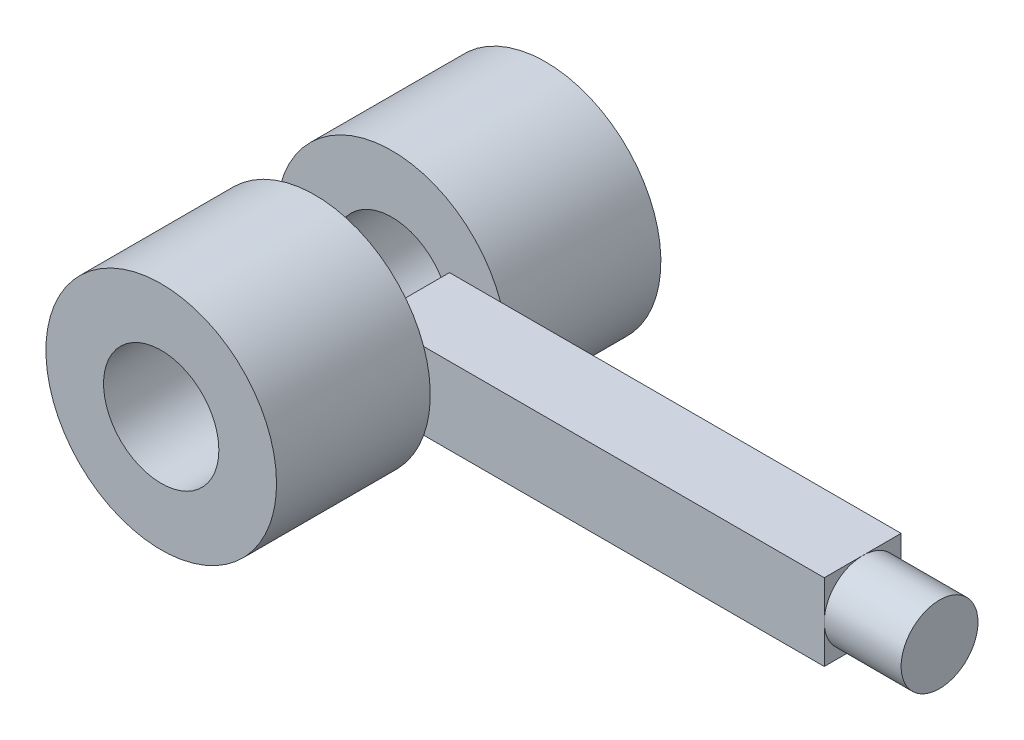
SolidWorks part; units mm, degrees
ref_plane "Front Plane" through (0, 0, 0) normal (0, 0, 1) x (1, 0, 0)
ref_plane "Top Plane" through (0, 0, 0) normal (0, 1, 0) x (1, 0, 0)
ref_plane "Right Plane" through (0, 0, 0) normal (1, 0, 0) x (0, 0, -1)
sketch "Sketch1" plane through (0, 0, 0) normal (0, 0, 1) x (1, 0, 0)
  circle A0 centre (0, 0) radius 3
  circle A1 centre (0, 0) radius 1.5
  dimension "D1" = 6
  dimension "D2" = 3
extrude "Boss-Extrude1" add sketch "Sketch1" along normal blind 4
ref_plane "Plane1" through (0, 0, -2) normal (0, 0, -1) x (-1, 0, 0)
sketch "Sketch2" plane through (0, 0, -2) normal (0, 0, -1) x (-1, 0, 0)
  circle A0 centre (0, 0) radius 1.5 construction
  circle A1 centre (0, 0) radius 3
  circle A2 centre (0, 0) radius 3
  circle A3 centre (0, 0) radius 1.5
  dimension "D1" = 0
extrude "Boss-Extrude2" add sketch "Sketch2" along normal blind 4 separate body
sketch "Sketch3" plane through (0, 0, -2) normal (0, 0, 1) x (1, 0, 0)
  line L1 (2.5, -1) -> (1.5, -1)
  line L2 (2.5, -1) -> (2.5, 1)
  line L3 (2.5, 1) -> (1.5, 1)
  line L4 (1.5, -1) -> (1.5, 1)
  line L5 (2.5, -1) -> (1.5, 1) construction
  line L6 (2.5, 1) -> (1.5, -1) construction
  circle A0 centre (0, 0) radius 1.5 construction
  point P7 (0, 0)
  point P8 (0, 0)
  point P10 (0, 0)
  dimension "D1" = 1
  dimension "D2" = 2
  dimension "D3" = 1
extrude "Boss-Extrude3" add sketch "Sketch3" along normal up to next
sketch "Sketch4" plane through (2.5, 0, 0) normal (1, 0, 0) x (0, 0, -1)
  line L4 (0, 1) -> (0, -1)
  line L5 (0, -1) -> (2, -1)
  line L6 (2, -1) -> (2, 1)
  line L7 (2, 1) -> (0, 1)
  line L8 (0, 1) -> (0, -1)
  line L9 (0, -1) -> (2, -1)
  line L10 (2, -1) -> (2, 1)
  line L11 (2, 1) -> (0, 1)
  dimension "D1" = 0
extrude "Boss-Extrude4" add sketch "Sketch4" along normal blind 10.75
sketch "Sketch6" plane through (13.25, 0, 0) normal (1, 0, 0) x (0, 0, -1)
  line L0 (2, 1) -> (0, 1) construction
  line L1 (2, -3.2056) -> (2, 3.2056) construction
  circle A0 centre (1, 0) radius 1
  dimension "D3" = 2
  dimension "D1" = 1
  dimension "D2" = 1
extrude "Boss-Extrude5" add sketch "Sketch6" along normal blind 2
